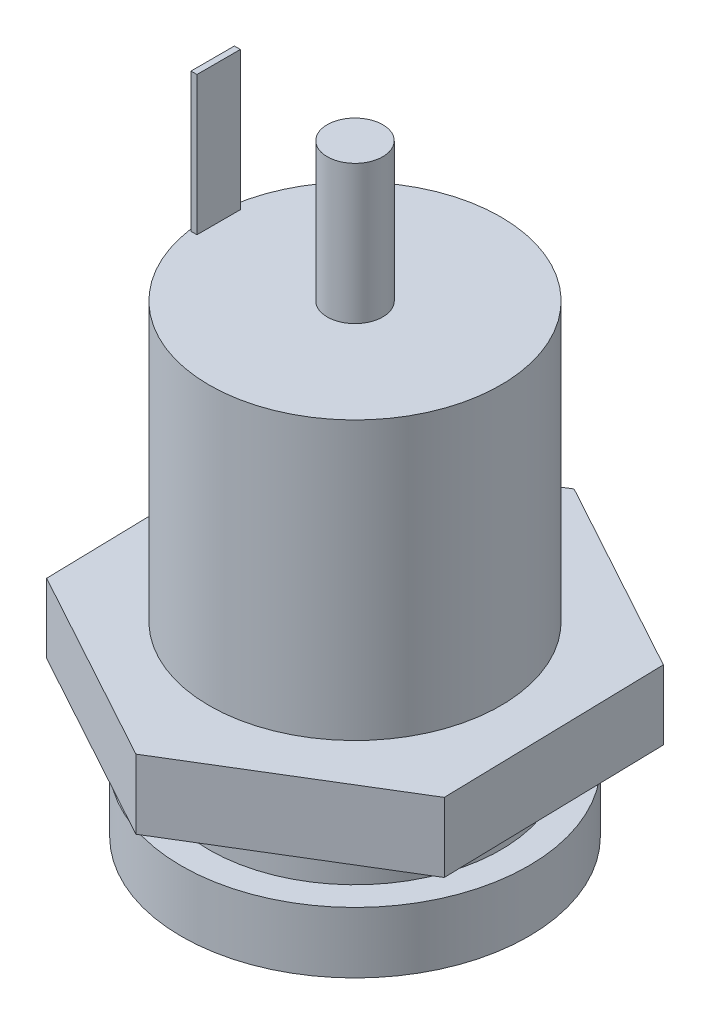
SolidWorks part; units mm, degrees
ref_plane "Спереди" through (0, 0, 0) normal (0, 0, 1) x (1, 0, 0)
ref_plane "Сверху" through (0, 0, 0) normal (0, 1, 0) x (1, 0, 0)
ref_plane "Справа" through (0, 0, 0) normal (1, 0, 0) x (0, 0, -1)
sketch "Эскиз1" plane through (0, 0, 0) normal (0, 1, 0) x (1, 0, 0)
  circle A0 centre (0, 0) radius 5.25
  dimension "D1" = 10.5
extrude "Бобышка-Вытянуть1" add sketch "Эскиз1" along normal blind 14.5
sketch "Эскиз2" plane through (0, 14.5, 0) normal (0, 1, 0) x (1, 0, 0)
  line L1 (-4.9115, 0.7811) -> (-5.1263, 0.7811)
  line L2 (-4.9115, 0.7811) -> (-4.9115, -0.7811)
  line L3 (-4.9115, -0.7811) -> (-5.1263, -0.7811)
  line L4 (-5.1263, 0.7811) -> (-5.1263, -0.7811)
  line L5 (-4.9115, 0.7811) -> (-5.1263, -0.7811) construction
  line L6 (-4.9115, -0.7811) -> (-5.1263, 0.7811) construction
  circle A0 centre (0, 0) radius 1
  point P3 (-5.0189, 0)
extrude "Бобышка-Вытянуть2" add sketch "Эскиз2" along normal blind 5
sketch "Эскиз3" plane through (0, 0, 0) normal (0, -1, 0) x (1, 0, 0)
  circle A0 centre (0, 0) radius 6.25
extrude "Бобышка-Вытянуть3" add sketch "Эскиз3" along normal blind 2.2
sketch "Эскиз4" plane through (0, 0, 0) normal (0, 1, 0) x (1, 0, 0)
  line L1 (7.0923, -3.8771) -> (6.9039, 4.2036)
  line L2 (6.9039, 4.2036) -> (-0.1885, 8.0807)
  line L3 (-0.1885, 8.0807) -> (-7.0923, 3.8771)
  line L4 (-7.0923, 3.8771) -> (-6.9039, -4.2036)
  line L5 (-6.9039, -4.2036) -> (0.1885, -8.0807)
  line L6 (0.1885, -8.0807) -> (7.0923, -3.8771)
  circle A0 centre (0, 0) radius 7 construction
  dimension "D1" = 14
extrude "Бобышка-Вытянуть4" add sketch "Эскиз4" along normal blind 2.5 from offset 2
sketch "Эскиз5" plane through (0, -2.2, 0) normal (0, -1, 0) x (1, 0, 0)
  circle A0 centre (0, 0) radius 2.25
extrude "Вырез-Вытянуть1" cut sketch "Эскиз5" against normal blind 11
